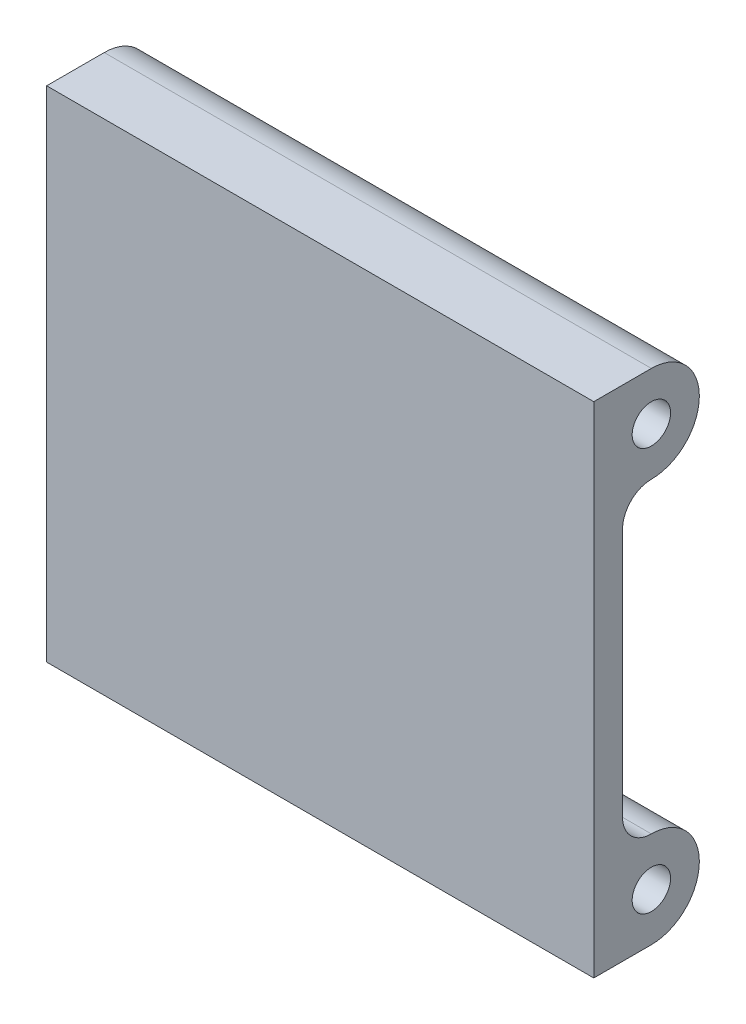
SolidWorks part; units mm, degrees
ref_plane "Front Plane" through (0, 0, 0) normal (0, 0, 1) x (1, 0, 0)
ref_plane "Top Plane" through (0, 0, 0) normal (0, 1, 0) x (1, 0, 0)
ref_plane "Right Plane" through (0, 0, 0) normal (1, 0, 0) x (0, 0, -1)
sketch "Sketch1" plane through (0, 0, 0) normal (1, 0, 0) x (0, 0, -1)
  line L0 (0, 0) -> (6, 0)
  line L1 (3, 13) -> (3, 39)
  line L2 (3, 26) -> (0, 26) construction
  line L3 (0, 52) -> (0, 0)
  line L4 (0, 52) -> (6, 52)
  arc A0 (6, 0) -> (6, 10) centre (6, 5) ccw
  arc A1 (6, 10) -> (3, 13) centre (6, 13) cw
  circle A2 centre (6, 5) radius 2
  circle A3 centre (6, 47) radius 2
  arc A4 (6, 42) -> (3, 39) centre (6, 39) ccw
  arc A5 (6, 52) -> (6, 42) centre (6, 47) cw
  dimension "D3" = 5
  dimension "D4" = 3
  dimension "D5" = 4
  dimension "D1" = 52
  dimension "D2" = 3
extrude "Boss-Extrude1" add sketch "Sketch1" along normal mid plane 57
